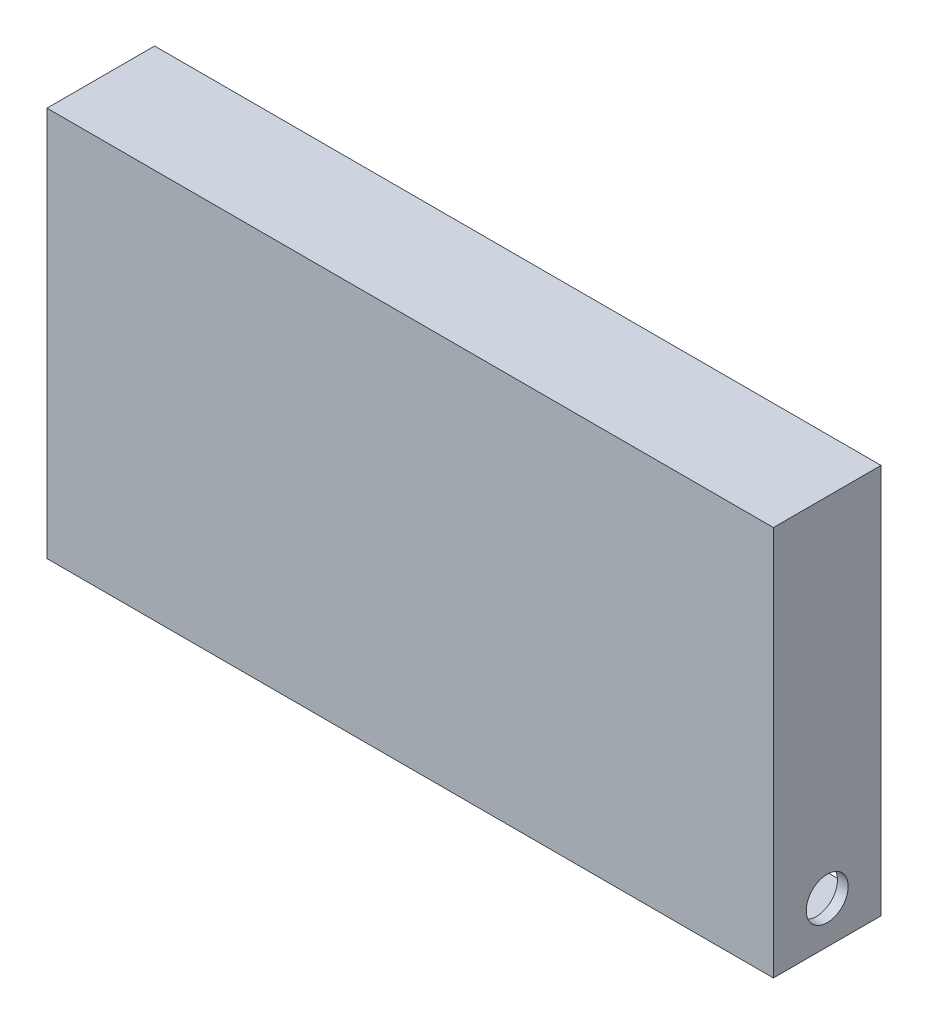
SolidWorks part; units mm, degrees
ref_plane "Front Plane" through (0, 0, 0) normal (0, 0, 1) x (1, 0, 0)
ref_plane "Top Plane" through (0, 0, 0) normal (0, 1, 0) x (1, 0, 0)
ref_plane "Right Plane" through (0, 0, 0) normal (1, 0, 0) x (0, 0, -1)
sketch "Sketch3" plane through (0, 0, 0) normal (0, 0, 1) x (1, 0, 0)
  line L1 (-67.5, -36.25) -> (67.5, -36.25)
  line L2 (-67.5, -36.25) -> (-67.5, 36.25)
  line L3 (-67.5, 36.25) -> (67.5, 36.25)
  line L4 (67.5, -36.25) -> (67.5, 36.25)
  line L5 (-67.5, -36.25) -> (67.5, 36.25) construction
  line L6 (-67.5, 36.25) -> (67.5, -36.25) construction
  point P0 (0, 0)
  dimension "D1" = 135
  dimension "D2" = 72.5
extrude "Boss-Extrude1" add sketch "Sketch3" along normal blind 20
sketch "Sketch4" plane through (0, 0, 0) normal (0, 0, -1) x (-1, 0, 0)
  line L0 (-67.5, 36.25) -> (67.5, 36.25) construction
  line L1 (-65.5, 34.25) -> (65.5, 34.25)
  line L2 (-65.5, 34.25) -> (-65.5, -34.25)
  line L3 (-65.5, -34.25) -> (65.5, -34.25)
  line L4 (65.5, 34.25) -> (65.5, -34.25)
  line L5 (-65.5, 34.25) -> (65.5, -34.25) construction
  line L6 (-65.5, -34.25) -> (65.5, 34.25) construction
  line L7 (-67.5, -36.25) -> (-67.5, 36.25) construction
  point P0 (0, 0)
  dimension "D1" = 2
  dimension "D2" = 2
extrude "Cut-Extrude1" cut sketch "Sketch4" against normal blind 18
sketch "Sketch5" plane through (0, 0, 18) normal (0, 0, -1) x (-1, 0, 0)
  line L0 (-65.5, 34.25) -> (-65.5, -34.25) construction
  line L1 (-65.5, 21.75) -> (-43.7, 21.75)
  line L2 (-65.5, 21.75) -> (-65.5, -21.75)
  line L3 (-65.5, -21.75) -> (-43.7, -21.75)
  line L4 (-43.7, 21.75) -> (-43.7, -21.75)
  line L5 (-65.5, -34.25) -> (65.5, -34.25) construction
  dimension "D1" = 21.8
  dimension "D2" = 43.5
  dimension "D3" = 12.5
sketch "Sketch6" plane through (0, 0, 18) normal (0, 0, -1) x (-1, 0, 0)
  line L0 (-65.5, 34.25) -> (-65.5, -34.25) construction
  line L1 (-65.5, 22.95) -> (-42.5, 22.95)
  line L2 (-65.5, 22.95) -> (-65.5, -22.95)
  line L3 (-65.5, -22.95) -> (-42.5, -22.95)
  line L4 (-42.5, 22.95) -> (-42.5, -22.95)
  line L5 (-65.5, 21.75) -> (-43.7, 21.75) construction
  line L6 (-43.7, 21.75) -> (-43.7, -21.75) construction
  line L7 (-65.5, -21.75) -> (-43.7, -21.75) construction
  dimension "D1" = 1.2
  dimension "D2" = 1.2
  dimension "D3" = 1.2
extrude "Boss-Extrude2" add sketch "Sketch6" along normal blind 8
extrude "Cut-Extrude2" cut sketch "Sketch5" along direction (0, 0, -1) on the side of the normal blind 18
sketch "Sketch7" plane through (0, 0, 18) normal (0, 0, -1) x (-1, 0, 0)
  line L1 (-65.5, -34.25) -> (65.5, -34.25) construction
  line L2 (-42.5, -22.95) -> (-43.7, -22.95)
  line L3 (-42.5, -22.95) -> (-42.5, -31.25)
  line L4 (-42.5, -31.25) -> (-43.7, -31.25)
  line L5 (-43.7, -22.95) -> (-43.7, -31.25)
  line L6 (65.5, 34.25) -> (-65.5, 34.25) construction
  line L7 (-42.5, 22.95) -> (-43.7, 22.95)
  line L8 (-42.5, 22.95) -> (-42.5, 34.25)
  line L9 (-42.5, 34.25) -> (-43.7, 34.25)
  line L10 (-43.7, 22.95) -> (-43.7, 34.25)
  dimension "D1" = 1.2
  dimension "D2" = 3
  dimension "D3" = 1.2
extrude "Boss-Extrude5" add sketch "Sketch7" along normal up to vertex
sketch "Sketch9" plane through (0, 0, 18) normal (0, 0, -1) x (-1, 0, 0)
  line L0 (65.5, 34.25) -> (-42.5, 34.25) construction
  line L1 (24.95, 34.25) -> (26.15, 34.25)
  line L2 (24.95, 34.25) -> (24.95, -31.25)
  line L3 (24.95, -31.25) -> (26.15, -31.25)
  line L4 (26.15, 34.25) -> (26.15, -31.25)
  line L5 (-65.5, -34.25) -> (65.5, -34.25) construction
  line L6 (-42.5, -31.25) -> (-42.5, 34.25) construction
  dimension "D1" = 3
  dimension "D2" = 1.2
  dimension "D3" = 67.45
extrude "Boss-Extrude6" add sketch "Sketch9" along normal up to surface (8 mm away) up to face at (50.7667, 0.5, 10)
sketch "Sketch10" plane through (0, 0, 18) normal (0, 0, -1) x (-1, 0, 0)
  line L0 (26.15, -31.25) -> (26.15, 34.25) construction
  line L1 (26.15, 16.8) -> (51.75, 16.8)
  line L2 (26.15, 16.8) -> (26.15, -16.8)
  line L3 (26.15, -16.8) -> (51.75, -16.8)
  line L4 (51.75, 16.8) -> (51.75, -16.8)
  line L5 (65.5, 34.25) -> (26.15, 34.25) construction
  line L6 (-65.5, -34.25) -> (65.5, -34.25) construction
  dimension "D1" = 25.6
  dimension "D2" = 33.6
  dimension "D3" = 17.45
  dimension "D4" = 17.45
sketch "Sketch11" plane through (0, 0, 18) normal (0, 0, -1) x (-1, 0, 0)
  line L0 (26.15, -31.25) -> (26.15, 34.25) construction
  line L1 (26.15, 18) -> (52.95, 18)
  line L2 (26.15, 18) -> (26.15, -18)
  line L3 (26.15, -18) -> (52.95, -18)
  line L4 (52.95, 18) -> (52.95, -18)
  line L5 (26.15, 16.8) -> (51.75, 16.8) construction
  line L6 (26.15, -16.8) -> (51.75, -16.8) construction
  line L7 (51.75, 16.8) -> (51.75, -16.8) construction
  dimension "D1" = 1.2
  dimension "D2" = 1.2
  dimension "D3" = 1.2
extrude "Boss-Extrude7" add sketch "Sketch11" along normal up to surface (8 mm away) up to face at (-25.55, 1.5, 10)
extrude "Cut-Extrude3" cut sketch "Sketch10" along normal up to surface (8 mm away) up to face at (-32.55, 0.75, 10)
sketch "Sketch13" plane through (-52.95, 0, 0) normal (-1, 0, 0) x (0, 0, 1)
  line L1 (10, 16.8) -> (18, 16.8)
  line L2 (10, 16.8) -> (10, -16.8)
  line L3 (10, -16.8) -> (18, -16.8)
  line L4 (18, 16.8) -> (18, -16.8)
extrude "Cut-Extrude4" cut sketch "Sketch13" against normal up to surface (1.2 mm away) up to face at (-51.75, 0, 14)
sketch "Sketch14" plane through (67.5, 0, 0) normal (1, 0, 0) x (0, 0, -1)
  line L0 (-20, -36.25) -> (0, -36.25) construction
  line L1 (-20, -36.25) -> (-20, 36.25) construction
  line L2 (0, -36.25) -> (0, 36.25) construction
  circle A0 centre (-10, -28.45) radius 3.9
  dimension "D1" = 7.8
  dimension "D3" = 10
  dimension "D4" = 10
  dimension "D2" = 7.8
extrude "Cut-Extrude5" cut sketch "Sketch14" against normal up to surface (2 mm away) up to face at (65.5, 0, 12.3333)
sketch "Sketch15" plane through (-67.5, 0, 0) normal (-1, 0, 0) x (0, 0, 1)
  line L0 (20, 36.25) -> (0, 36.25) construction
  line L3 (0, 36.25) -> (0, -36.25) construction
  line L4 (20, 36.25) -> (20, -36.25) construction
  circle A0 centre (10, 26.25) radius 5.9
  circle A1 centre (10, 6.25) radius 5.9
  circle A2 centre (10, -13.75) radius 5.9
  dimension "D1" = 11.8
  dimension "D3" = 10
  dimension "D4" = 10
  dimension "D6" = 11.8
  dimension "D7" = 11.8
  dimension "D2" = 10
  dimension "D5" = 20
  dimension "D8" = 20
extrude "Cut-Extrude6" cut sketch "Sketch15" against normal up to surface (2 mm away) up to face at (-65.5, 0, 9)
sketch "Sketch18" plane through (0, 0, 18) normal (0, 0, -1) x (-1, 0, 0)
  line L0 (26.15, -16.8) -> (52.95, -16.8) construction
  line L1 (37.05, -11.8) -> (42.05, -11.8)
  line L2 (37.05, -11.8) -> (37.05, -16.8)
  line L3 (37.05, -16.8) -> (42.05, -16.8)
  line L4 (42.05, -11.8) -> (42.05, -16.8)
  line L5 (26.15, 16.8) -> (26.15, -16.8) construction
  line L6 (52.95, 16.8) -> (26.15, 16.8) construction
  line L7 (37.05, 16.8) -> (42.05, 16.8)
  line L8 (37.05, 16.8) -> (37.05, 11.8)
  line L9 (37.05, 11.8) -> (42.05, 11.8)
  line L10 (42.05, 16.8) -> (42.05, 11.8)
  dimension "D1" = 5
  dimension "D2" = 5
  dimension "D3" = 10.9
  dimension "D4" = 10.9
  dimension "D5" = 5
  dimension "D6" = 5
  dimension "D7" = 10.9
extrude "Boss-Extrude8" add sketch "Sketch18" along normal blind 5
sketch "Sketch19" plane through (0, 0, 10) normal (0, 0, -1) x (-1, 0, 0)
  line L0 (52.95, -16.8) -> (14.9675, -16.8) construction
  line L1 (52.95, 16.8) -> (15.6954, 16.8) construction
  circle A0 centre (39.6638, -14.3) radius 1.5
  circle A1 centre (39.6638, 14.3) radius 1.5
  dimension "D1" = 3
  dimension "D4" = 3
  dimension "D2" = 2.5
  dimension "D3" = 2.5
extrude "Cut-Extrude7" cut sketch "Sketch19" against normal up to surface (8 mm away) up to face at (54.6, 28.6, 18)
sketch "Sketch20" plane through (0, 0, 18) normal (0, 0, -1) x (-1, 0, 0)
  line L0 (-43.7, -21.75) -> (-43.7, 21.75) construction
  line L1 (-43.7, 18.75) -> (-48.7, 18.75)
  line L2 (-43.7, 18.75) -> (-43.7, 13.75)
  line L3 (-43.7, 13.75) -> (-48.7, 13.75)
  line L4 (-48.7, 18.75) -> (-48.7, 13.75)
  line L5 (-43.7, 21.75) -> (-65.5, 21.75) construction
  line L6 (-65.5, 21.75) -> (-65.5, -21.75) construction
  line L7 (-65.5, -18.75) -> (-60.5, -18.75)
  line L8 (-65.5, -18.75) -> (-65.5, -13.75)
  line L9 (-65.5, -13.75) -> (-60.5, -13.75)
  line L10 (-60.5, -18.75) -> (-60.5, -13.75)
  line L11 (-65.5, -21.75) -> (-43.7, -21.75) construction
  dimension "D1" = 5
  dimension "D2" = 5
  dimension "D3" = 3
  dimension "D4" = 5
  dimension "D5" = 5
  dimension "D6" = 3
extrude "Boss-Extrude9" add sketch "Sketch20" along normal blind 5
sketch "Sketch21" plane through (0, 0, 13) normal (0, 0, -1) x (-1, 0, 0)
  line L0 (-43.7, 18.75) -> (-48.7, 18.75) construction
  line L1 (-60.5, -13.75) -> (-65.5, -13.75) construction
  line L2 (-60.5, -18.75) -> (-60.5, -13.75) construction
  line L3 (-43.7, 21.75) -> (-43.7, -21.75) construction
  circle A0 centre (-46.2, 16.25) radius 1.5
  circle A1 centre (-63, -16.25) radius 1.5
  dimension "D2" = 3
  dimension "D3" = 3
  dimension "D5" = 2.5
  dimension "D6" = 2.5
  dimension "D1" = 2.5
  dimension "D4" = 2.5
extrude "Cut-Extrude8" cut sketch "Sketch21" against normal up to surface (5 mm away) up to face at (54.6, 0, 18)
sketch "Sketch23" plane through (0, 0, 18) normal (0, 0, -1) x (-1, 0, 0)
  line L5 (24.95, 34.25) -> (24.95, -31.25) construction
  line L6 (-42.5, 34.25) -> (-35.5, 34.25)
  line L7 (-42.5, 34.25) -> (-42.5, 27.25)
  line L8 (-42.5, 27.25) -> (-35.5, 27.25)
  line L9 (-35.5, 34.25) -> (-35.5, 27.25)
  line L10 (24.95, 34.25) -> (17.95, 34.25)
  line L11 (24.95, 34.25) -> (24.95, 27.25)
  line L12 (24.95, 27.25) -> (17.95, 27.25)
  line L13 (17.95, 34.25) -> (17.95, 27.25)
  line L14 (24.95, -31.25) -> (17.95, -31.25)
  line L15 (24.95, -31.25) -> (24.95, -24.25)
  line L16 (24.95, -24.25) -> (17.95, -24.25)
  line L17 (17.95, -31.25) -> (17.95, -24.25)
  line L18 (-42.5, -31.25) -> (-42.5, 34.25) construction
  line L19 (-42.5, -31.25) -> (-35.5, -31.25)
  line L20 (-42.5, -31.25) -> (-42.5, -24.25)
  line L21 (-42.5, -24.25) -> (-35.5, -24.25)
  line L22 (-35.5, -31.25) -> (-35.5, -24.25)
  dimension "D1" = 7
  dimension "D2" = 7
  dimension "D3" = 7
  dimension "D4" = 7
  dimension "D5" = 7
  dimension "D6" = 7
  dimension "D7" = 65.5
  dimension "D8" = 7
  dimension "D9" = 7
  dimension "D10" = 65.5
extrude "Boss-Extrude10" add sketch "Sketch23" along normal blind 5
sketch "Sketch24" plane through (0, 0, 13) normal (0, 0, -1) x (-1, 0, 0)
  line L0 (65.5, 34.25) -> (-65.5, 34.25) construction
  line L1 (-42.5, -31.25) -> (-42.5, 34.25) construction
  line L2 (24.95, 34.25) -> (24.95, -31.25) construction
  line L3 (24.95, -24.25) -> (17.95, -24.25) construction
  line L4 (17.95, -24.25) -> (17.95, -31.25) construction
  line L5 (-35.5, -24.25) -> (-42.5, -24.25) construction
  line L6 (-35.5, -31.25) -> (-35.5, -24.25) construction
  circle A0 centre (-39, 30.75) radius 1.5
  circle A1 centre (21.45, 30.75) radius 1.5
  circle A2 centre (21.45, -27.75) radius 1.5
  circle A3 centre (-39, -27.75) radius 1.5
  dimension "D1" = 3
  dimension "D4" = 3
  dimension "D5" = 3.5
  dimension "D6" = 3.5
  dimension "D7" = 3
  dimension "D10" = 3
  dimension "D12" = 3.5
  dimension "D2" = 3.5
  dimension "D3" = 3.5
  dimension "D8" = 3.5
  dimension "D9" = 3.5
  dimension "D11" = 3.5
extrude "Cut-Extrude10" cut sketch "Sketch24" against normal blind 5
